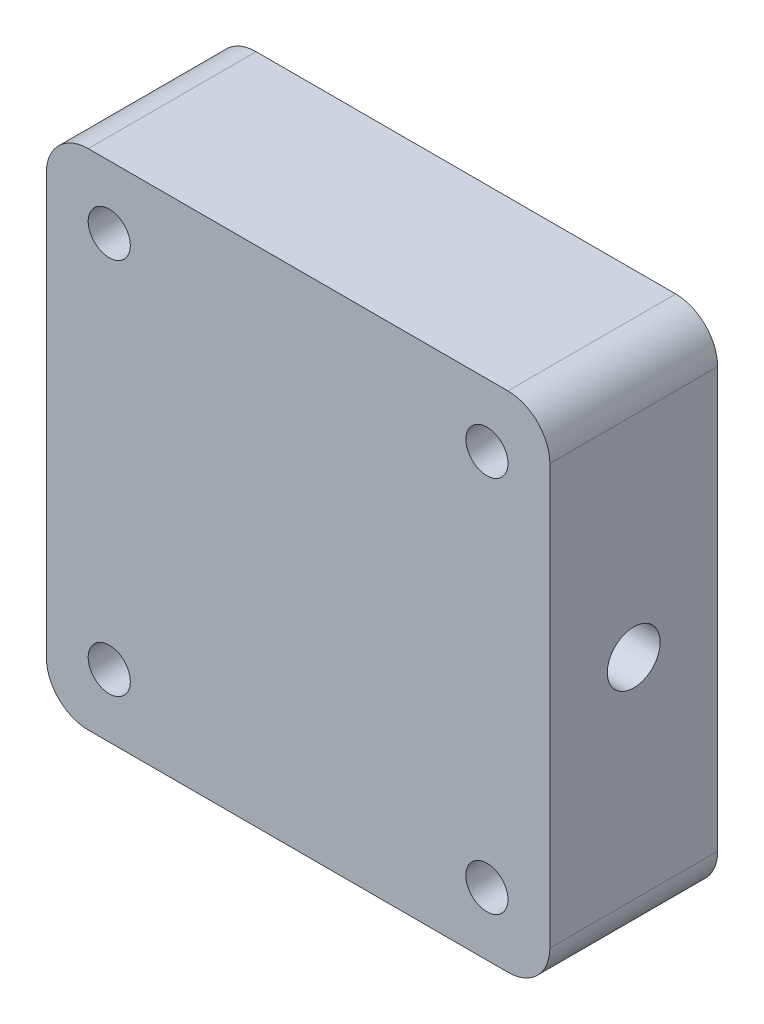
SolidWorks part; units mm, degrees
material "Plain Carbon Steel"
ref_plane "Front Plane" through (0, 0, 0) normal (0, 0, 1) x (1, 0, 0)
ref_plane "Top Plane" through (0, 0, 0) normal (0, 1, 0) x (1, 0, 0)
ref_plane "Right Plane" through (0, 0, 0) normal (1, 0, 0) x (0, 0, -1)
sketch "Sketch1" plane through (0, 0, 0) normal (0, 0, 1) x (1, 0, 0)
  line L1 (-31.75, 38.1) -> (31.75, 38.1)
  line L2 (-38.1, 31.75) -> (-38.1, -31.75)
  line L3 (-31.75, -38.1) -> (31.75, -38.1)
  line L4 (38.1, 31.75) -> (38.1, -31.75)
  line L5 (-38.1, 38.1) -> (38.1, -38.1) construction
  line L6 (-38.1, -38.1) -> (38.1, 38.1) construction
  line L7 (-28.575, 28.575) -> (28.575, 28.575) construction
  line L8 (-28.575, 28.575) -> (-28.575, -28.575) construction
  line L9 (-28.575, -28.575) -> (28.575, -28.575) construction
  line L10 (28.575, 28.575) -> (28.575, -28.575) construction
  line L11 (-28.575, 28.575) -> (28.575, -28.575) construction
  line L12 (-28.575, -28.575) -> (28.575, 28.575) construction
  circle A1 centre (-28.575, 28.575) radius 3.1877
  circle A2 centre (28.575, 28.575) radius 3.1877
  circle A3 centre (28.575, -28.575) radius 3.1877
  circle A4 centre (-28.575, -28.575) radius 3.1877
  arc A5 (-38.1, -31.75) -> (-31.75, -38.1) centre (-31.75, -31.75) ccw
  arc A6 (31.75, -38.1) -> (38.1, -31.75) centre (31.75, -31.75) ccw
  arc A7 (31.75, 38.1) -> (38.1, 31.75) centre (31.75, 31.75) cw
  arc A8 (-31.75, 38.1) -> (-38.1, 31.75) centre (-31.75, 31.75) ccw
  dimension "D4" = 6.3754
  dimension "D5" = 6.3754
  dimension "D6" = 6.3754
  dimension "D7" = 6.3754
  dimension "D9" = 6.35
  dimension "D1" = 76.2
  dimension "D2" = 76.2
  dimension "D8" = 9.525
extrude "Boss-Extrude1" add sketch "Sketch1" along normal blind 25.4
sketch "Sketch3" plane through (38.1, 0, 0) normal (1, 0, 0) x (0, 0, -1)
  line L0 (-25.4, 31.75) -> (0, 31.75) construction
  circle A0 centre (-12.7, 0) radius 4
  point P5 (-12.7, 31.75)
  dimension "D1" = 8
extrude "Cut-Extrude1" cut sketch "Sketch3" against normal through all
scale "Scale1" scale about centroid uniform scaling yes scale factor 0.66
